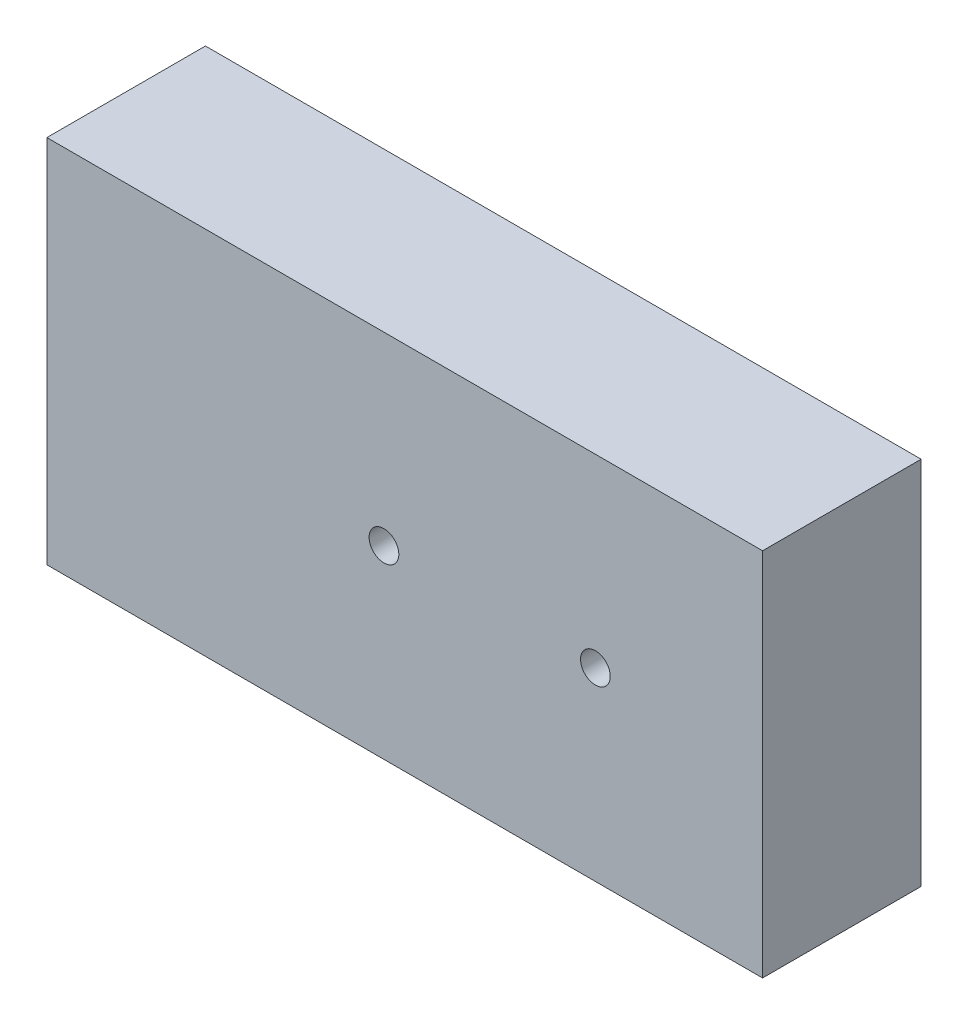
SolidWorks part; units mm, degrees
material "Pine"
ref_plane "Front Plane" through (0, 0, 0) normal (0, 0, 1) x (1, 0, 0)
ref_plane "Top Plane" through (0, 0, 0) normal (0, 1, 0) x (1, 0, 0)
ref_plane "Right Plane" through (0, 0, 0) normal (1, 0, 0) x (0, 0, -1)
sketch "Sketch1" plane through (0, 0, 0) normal (1, 0, 0) x (0, 0, -1)
  line L1 (0, 0) -> (38.1, 0)
  line L2 (0, 0) -> (0, 88.9)
  line L3 (0, 88.9) -> (38.1, 88.9)
  line L4 (38.1, 0) -> (38.1, 88.9)
  dimension "D1" = 38.1
  dimension "D2" = 88.9
extrude "Boss-Extrude1" add sketch "Sketch1" along normal blind 171.958
sketch "Sketch3" plane through (0, 0, -38.1) normal (0, 0, -1) x (-1, 0, 0)
  line L0 (-171.958, 0) -> (-171.958, 88.9) construction
  line L1 (-171.958, 0) -> (0, 0) construction
  circle A0 centre (-131.793, 44.45) radius 3.5719
  circle A1 centre (-80.993, 44.45) radius 3.5719
  dimension "D5" = 7.1437
  dimension "D6" = 7.1437
  dimension "D1" = 40.165
  dimension "D2" = 50.8
  dimension "D3" = 44.45
  dimension "D4" = 44.45
extrude "Cut-Extrude1" cut sketch "Sketch3" against normal through all
